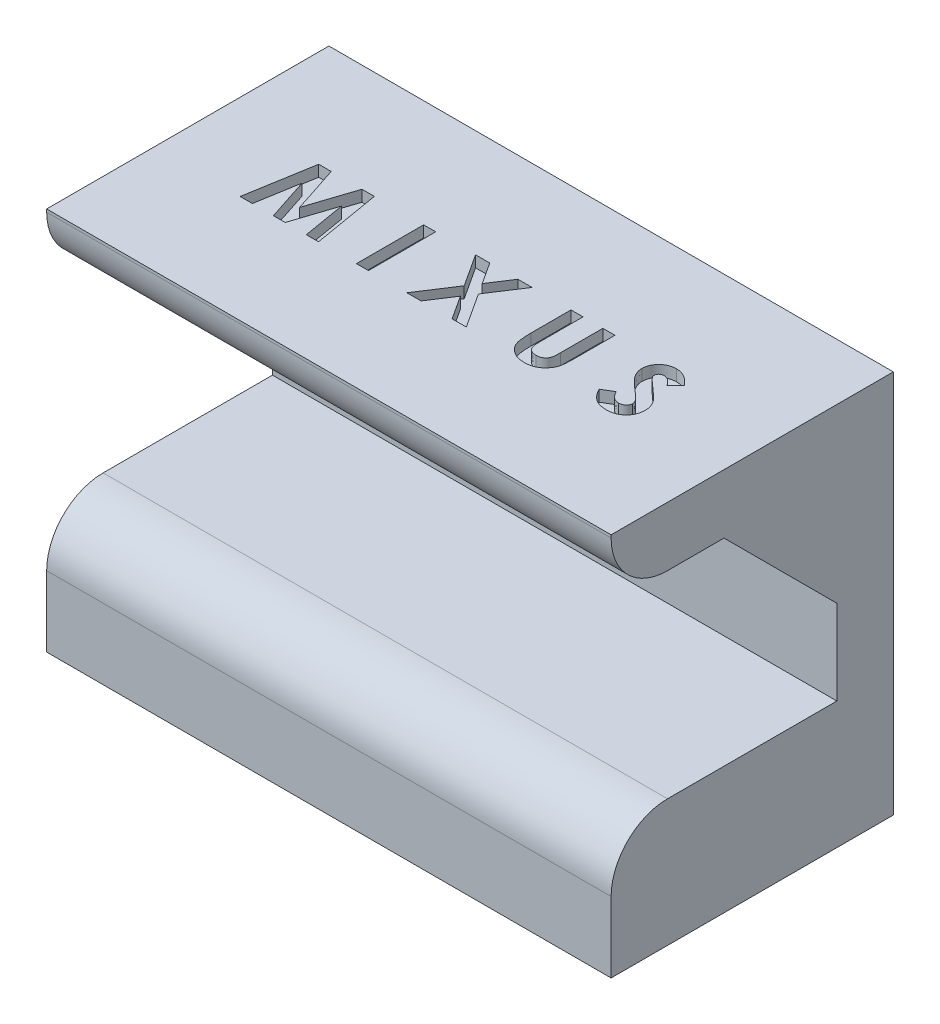
SolidWorks part; units mm, degrees
ref_plane "Plan de face" through (0, 0, 0) normal (0, 0, 1) x (1, 0, 0)
ref_plane "Plan de dessus" through (0, 0, 0) normal (0, 1, 0) x (1, 0, 0)
ref_plane "Plan de droite" through (0, 0, 0) normal (1, 0, 0) x (0, 0, -1)
sketch "Esquisse1" plane through (0, 0, 0) normal (0, 0, 1) x (1, 0, 0)
  line L0 (-50, 34) -> (50, -34) construction
  line L1 (-50, 34) -> (50, 34)
  line L2 (-50, 34) -> (-50, -34)
  line L3 (-50, -34) -> (50, -34)
  line L4 (50, 34) -> (50, -34)
  line L5 (-50, -34) -> (50, 34) construction
  point P4 (0, 0)
  dimension "D1" = 100
  dimension "D2" = 68
extrude "Boss.-Extru.1" add sketch "Esquisse1" along normal mid plane 50
sketch "Esquisse2" plane through (0, 0, 25) normal (0, 0, 1) x (1, 0, 0)
  line L0 (-50, 34) -> (-50, -34) construction
  line L1 (-50, 23.5) -> (50, 23.5)
  line L2 (-50, 23.5) -> (-50, -11.5)
  line L3 (-50, -11.5) -> (50, -11.5)
  line L4 (50, 23.5) -> (50, -11.5)
  line L5 (50, -34) -> (50, 34) construction
  line L6 (-50, -34) -> (50, -34) construction
  point P8 (-50, 6)
  dimension "D1" = 40
  dimension "D2" = 35
extrude "Enlèv. mat.-Extru.1" cut sketch "Esquisse2" against normal blind 40
hole_wizard "Fraisage pour vis à tête fraisée bombée #61" positions "Esquisse4" profile "Esquisse3" countersink size "#6" standard "Ansi Inch" end condition through all
sketch "Esquisse4" plane through (0, 0, -15) normal (0, 0, 1) x (1, 0, 0)
  line L0 (-50, -34) -> (50, -34) construction
  line L1 (-50, 23.5) -> (-50, -11.5) construction
  line L2 (50, -11.5) -> (50, 23.5) construction
  point P0 (-20, 6)
  point P1 (20, 6)
  dimension "D1" = 40
  dimension "D2" = 30
  dimension "D3" = 30
sketch "Esquisse3" plane through (-20, 6, -15) normal (1, 0, 0) x (0, -1, 0)
  line L0 (0, 0) -> (0, 10)
  line L1 (0, 10) -> (1.8986, 10)
  line L2 (1.8986, 10) -> (1.8986, 1.892)
  line L3 (1.8986, 1.892) -> (3.5433, 0)
  line L5 (3.5433, 0) -> (0, 0)
  line L6 (-1.8986, 1.892) -> (-3.5433, 0) construction
  line L11 (0, -6.35) -> (0, 107.95) construction
  dimension "Diamètre du perçage jusqu'au prochain" = 3.7973
  dimension "Profondeur du perçage jusqu'au prochain" = 10
  dimension "Diamètre du fraisage entrant" = 7.0866
  dimension "Angle du fraisage entrant" = 82
fillet "Congé1" radius 10 2 edges at (0, 23.5, 25) (0, -11.5, 25)
sketch "Esquisse5" plane through (50, 0, 0) normal (1, 0, 0) x (0, 0, -1)
  line L0 (-5, 23.5) -> (15, 3.5)
  line L1 (15, 23.5) -> (-15, 23.5) construction
  line L2 (15, -11.5) -> (15, 23.5) construction
  dimension "D1" = 20
  dimension "D2" = 20
rib "Nervure1" sketch "Esquisse5" sketch "Esquisse5" thickness 5 extrusion direction parallel to sketch draft on no parameters "D1"=5
mirror "Symétrie1" about plane through (0, 0, 0) normal (1, 0, 0) of "Nervure1"
sketch "Esquisse6" plane through (0, 34, 0) normal (0, 1, 0) x (1, 0, 0)
  text T0 "<b>MIXUS</b>" font "Century Gothic" height in points 45
extrude "Enlèv. mat.-Extru.2" cut sketch "Esquisse6" against normal blind 2
